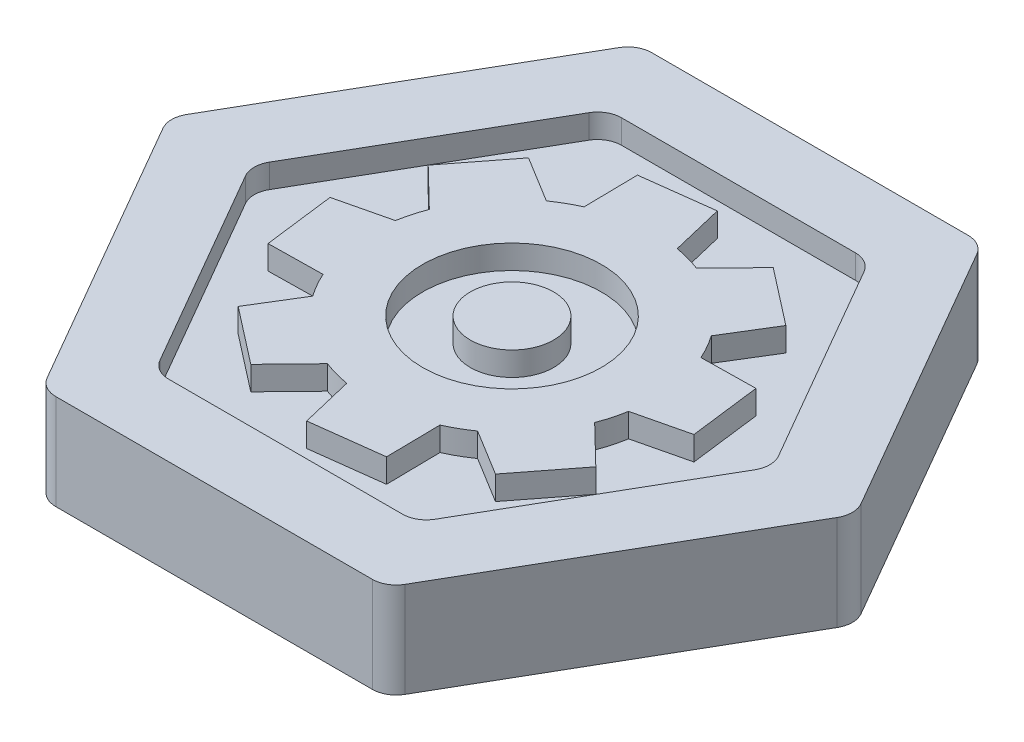
SolidWorks part; units mm, degrees
ref_plane "前视基准面" through (0, 0, 0) normal (0, 0, 1) x (1, 0, 0)
ref_plane "上视基准面" through (0, 0, 0) normal (0, 1, 0) x (1, 0, 0)
ref_plane "右视基准面" through (0, 0, 0) normal (1, 0, 0) x (0, 0, -1)
sketch "草图1" plane through (0, 0, 0) normal (0, 1, 0) x (1, 0, 0)
  line L1 (14.4338, 0) -> (7.2169, 12.5)
  line L2 (7.2169, 12.5) -> (-7.2169, 12.5)
  line L3 (-7.2169, 12.5) -> (-14.4338, 0)
  line L4 (-14.4338, 0) -> (-7.2169, -12.5)
  line L5 (-7.2169, -12.5) -> (7.2169, -12.5)
  line L6 (7.2169, -12.5) -> (14.4338, 0)
  circle A0 centre (0, 0) radius 12.5 construction
  dimension "D1" = 25
extrude "凸台-拉伸1" add sketch "草图1" along normal blind 4
sketch "草图2" plane through (0, 4, 0) normal (0, 1, 0) x (1, 0, 0)
  line L0 (5.4848, -9.5) -> (10.9697, 0)
  line L1 (10.9697, 0) -> (5.4848, 9.5)
  line L2 (5.4848, 9.5) -> (-5.4848, 9.5)
  line L3 (-5.4848, 9.5) -> (-10.9697, 0)
  line L4 (-10.9697, 0) -> (-5.4848, -9.5)
  line L5 (-5.4848, -9.5) -> (5.4848, -9.5)
  line L6 (7.2169, -12.5) -> (14.4338, 0)
  line L7 (14.4338, 0) -> (7.2169, 12.5)
  line L8 (7.2169, 12.5) -> (-7.2169, 12.5)
  line L9 (-7.2169, 12.5) -> (-14.4338, 0)
  line L10 (-14.4338, 0) -> (-7.2169, -12.5)
  line L11 (-7.2169, -12.5) -> (7.2169, -12.5)
  line L12 (7.2169, -12.5) -> (14.4338, 0)
  line L13 (14.4338, 0) -> (7.2169, 12.5)
  line L14 (7.2169, 12.5) -> (-7.2169, 12.5)
  line L15 (-7.2169, 12.5) -> (-14.4338, 0)
  line L16 (-14.4338, 0) -> (-7.2169, -12.5)
  line L17 (-7.2169, -12.5) -> (7.2169, -12.5)
  dimension "D1" = 0
  dimension "D2" = 3
extrude "切除-拉伸1" cut sketch "草图2" against normal blind 1 contours L0 L1 L2 L3 L4 L5
sketch "草图3" plane through (0, 3, 0) normal (0, 1, 0) x (1, 0, 0)
  line L5 (7.7503, 2.4864) -> (5.4759, 2.4524)
  line L6 (7.7503, 2.4864) -> (8.1246, -0.4901)
  line L16 (8.1246, -0.4901) -> (5.9126, -1.0203)
  line L17 (7.9375, 0.9982) -> (5.9531, 0.7486) construction
  line L18 (7.2385, -3.7221) -> (5.6062, -2.138)
  line L19 (7.2385, -3.7221) -> (5.3984, -6.0916)
  line L20 (5.3984, -6.0916) -> (3.4594, -4.9023)
  line L21 (6.3185, -4.9068) -> (4.7388, -3.6801) construction
  line L22 (2.4864, -7.7503) -> (2.4524, -5.4759)
  line L23 (2.4864, -7.7503) -> (-0.4901, -8.1246)
  line L24 (-0.4901, -8.1246) -> (-1.0203, -5.9126)
  line L25 (0.9982, -7.9375) -> (0.7486, -5.9531) construction
  line L26 (-3.7221, -7.2385) -> (-2.138, -5.6062)
  line L27 (-3.7221, -7.2385) -> (-6.0916, -5.3984)
  line L28 (-6.0916, -5.3984) -> (-4.9023, -3.4594)
  line L29 (-4.9068, -6.3185) -> (-3.6801, -4.7388) construction
  line L30 (-7.7503, -2.4864) -> (-5.4759, -2.4524)
  line L31 (-7.7503, -2.4864) -> (-8.1246, 0.4901)
  line L32 (-8.1246, 0.4901) -> (-5.9126, 1.0203)
  line L33 (-7.9375, -0.9982) -> (-5.9531, -0.7486) construction
  line L34 (-7.2385, 3.7221) -> (-5.6062, 2.138)
  line L35 (-7.2385, 3.7221) -> (-5.3984, 6.0916)
  line L36 (-5.3984, 6.0916) -> (-3.4594, 4.9023)
  line L37 (-6.3185, 4.9068) -> (-4.7388, 3.6801) construction
  line L38 (-2.4864, 7.7503) -> (-2.4524, 5.4759)
  line L39 (-2.4864, 7.7503) -> (0.4901, 8.1246)
  line L40 (0.4901, 8.1246) -> (1.0203, 5.9126)
  line L41 (-0.9982, 7.9375) -> (-0.7486, 5.9531) construction
  line L42 (3.7221, 7.2385) -> (2.138, 5.6062)
  line L43 (3.7221, 7.2385) -> (6.0916, 5.3984)
  line L44 (6.0916, 5.3984) -> (4.9023, 3.4594)
  line L45 (4.9068, 6.3185) -> (3.6801, 4.7388) construction
  circle A0 centre (0, 0) radius 6
  circle A2 centre (0, 0) radius 3.75
  circle A3 centre (0, 0) radius 1.75
  point P43 (0, 0)
  dimension "D1" = 12
  dimension "D7" = 3.5
  dimension "D2" = 3
  dimension "D3" = 2
  dimension "D4" = 3.5
  dimension "D6" = 2.25
  dimension "D5" = 8
extrude "凸台-拉伸2" add sketch "草图3" along normal blind 1 contours A0 | A0 L16 L6 L5 | A0 L20 L19 L18 | A0 L24 L23 L22 | A0 L28 L27 L26 | A0 L32 L31 L30 | A0 L36 L35 L34 | A0 L40 L39 L38 | A0 L44 L43 L42 | A3
fillet "圆角1" radius 1 12 edges at (-10.9697, 3.5, 0) (-5.4848, 3.5, 9.5) (5.4848, 3.5, 9.5) (10.9697, 3.5, 0) (5.4848, 3.5, -9.5) (-5.4848, 3.5, -9.5) (-14.4338, 2, 0) (-7.2169, 2, -12.5) (7.2169, 2, -12.5) (14.4338, 2, 0) (7.2169, 2, 12.5) (-7.2169, 2, 12.5)
